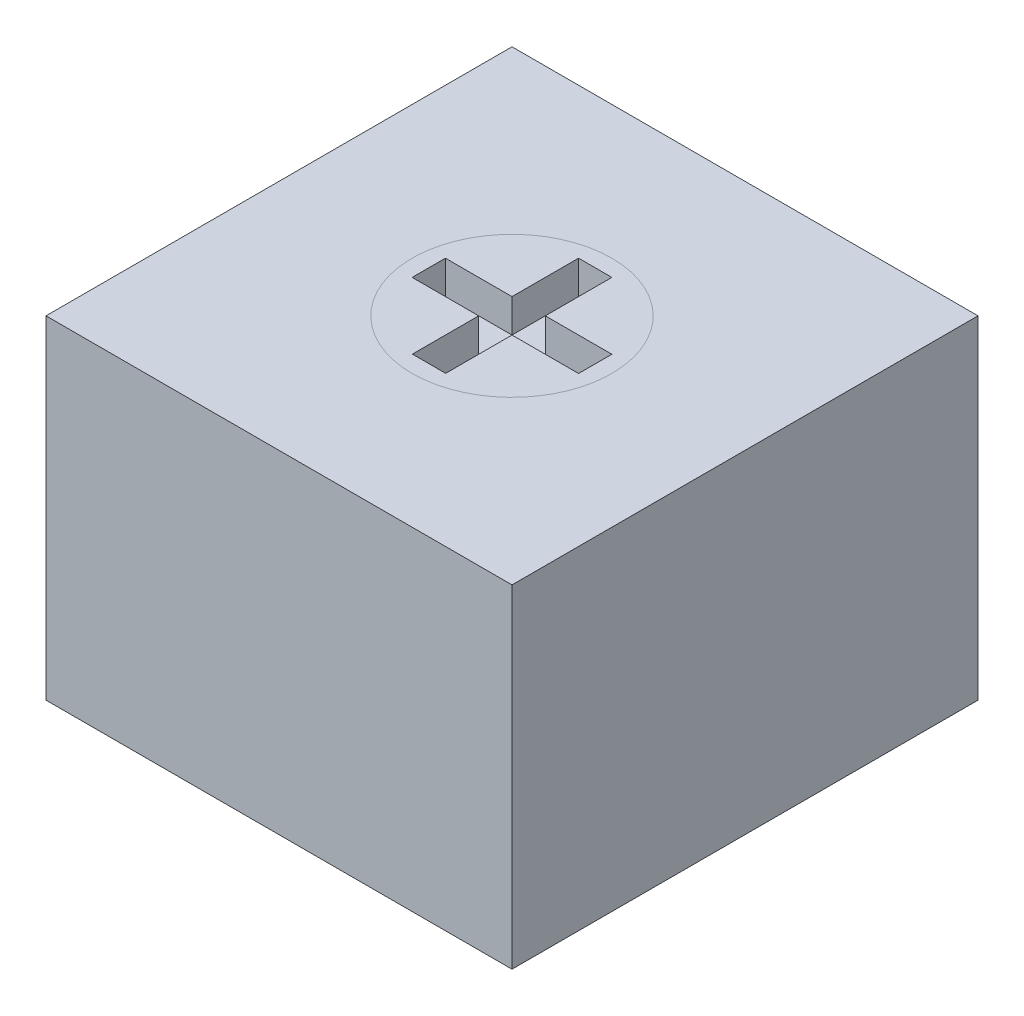
SolidWorks part; units mm, degrees
ref_plane "前视基准面" through (0, 0, 0) normal (0, 0, 1) x (1, 0, 0)
ref_plane "上视基准面" through (0, 0, 0) normal (0, 1, 0) x (1, 0, 0)
ref_plane "右视基准面" through (0, 0, 0) normal (1, 0, 0) x (0, 0, -1)
sketch "草图1" plane through (0, 0, 0) normal (0, 1, 0) x (1, 0, 0)
  line L1 (-19.8384, 17.54) -> (-12.8384, 17.54)
  line L2 (-19.8384, 17.54) -> (-19.8384, 10.54)
  line L3 (-19.8384, 10.54) -> (-12.8384, 10.54)
  line L4 (-12.8384, 17.54) -> (-12.8384, 10.54)
extrude "凸台-拉伸1" add sketch "草图1" along normal blind 5
sketch "草图2" plane through (0, 5, 0) normal (0, 1, 0) x (1, 0, 0)
  line L0 (-12.8384, 10.54) -> (-12.8384, 17.54) construction
  line L1 (-12.8384, 17.54) -> (-19.8384, 17.54) construction
  circle A0 centre (-16.3384, 14.04) radius 1.5
  dimension "D1" = 3.5
  dimension "D2" = 3.5
extrude "切除-拉伸1" cut sketch "草图2" against normal blind 3
sketch "草图3" plane through (0, 2, 0) normal (0, 1, 0) x (1, 0, 0)
  circle A0 centre (-16.3384, 14.04) radius 1.5
extrude "凸台-拉伸2" add sketch "草图3" along normal blind 3 separate body
sketch "草图4" plane through (0, 5, 0) normal (0, 1, 0) x (1, 0, 0)
  line L0 (-19.8384, 17.54) -> (-19.8384, 10.54) construction
  line L1 (-17.5884, 14.29) -> (-16.5884, 14.29)
  line L2 (-17.5884, 14.29) -> (-17.5884, 13.79)
  line L3 (-17.5884, 13.79) -> (-16.5884, 13.79)
  line L4 (-15.0884, 14.29) -> (-15.0884, 13.79)
  line L5 (-12.8384, 17.54) -> (-19.8384, 17.54) construction
  line L6 (-19.8384, 10.54) -> (-12.8384, 10.54) construction
  line L7 (-12.8384, 10.54) -> (-12.8384, 17.54) construction
  line L8 (-16.5884, 15.29) -> (-16.0884, 15.29)
  line L9 (-16.5884, 15.29) -> (-16.5884, 14.29)
  line L10 (-16.5884, 12.7938) -> (-16.0884, 12.7938)
  line L11 (-16.0884, 15.29) -> (-16.0884, 14.29)
  line L12 (-16.0884, 14.29) -> (-15.0884, 14.29)
  line L13 (-16.0884, 13.79) -> (-15.0884, 13.79)
  line L14 (-16.5884, 13.79) -> (-16.5884, 12.7938)
  line L15 (-16.0884, 13.79) -> (-16.0884, 12.7938)
  point P4 (-17.5884, 14.04)
  dimension "D1" = 2.25
  dimension "D2" = 3.25
  dimension "D3" = 3.25
  dimension "D4" = 3.25
  dimension "D5" = 3.25
  dimension "D6" = 2.25
extrude "切除-拉伸2" cut sketch "草图4" against normal blind 0.5
